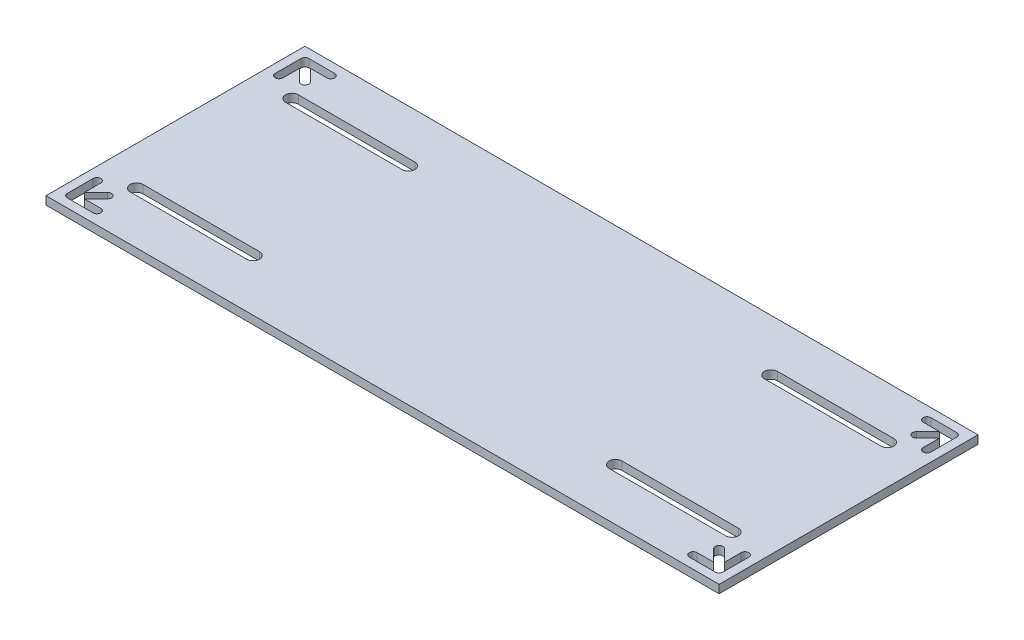
SolidWorks part; units mm, degrees
ref_plane "Front Plane" through (0, 0, 0) normal (0, 0, 1) x (1, 0, 0)
ref_plane "Top Plane" through (0, 0, 0) normal (0, 1, 0) x (1, 0, 0)
ref_plane "Right Plane" through (0, 0, 0) normal (1, 0, 0) x (0, 0, -1)
sketch "Sketch1" plane through (0, 0, 0) normal (0, 1, 0) x (1, 0, 0)
  line L0 (0, -50) -> (0, 50) construction
  line L1 (130, -50) -> (-130, -50)
  line L2 (130, -50) -> (130, 50)
  line L3 (130, 50) -> (-130, 50)
  line L4 (-130, -50) -> (-130, 50)
  line L5 (130, -50) -> (-130, 50) construction
  line L6 (130, 50) -> (-130, -50) construction
  line L7 (-130, 0) -> (130, 0) construction
  point P0 (0, 0)
  dimension "D1" = 260
  dimension "D2" = 100
extrude "Base" add sketch "Sketch1" along normal blind 3.175 contours L3 L4 L1 L2
sketch "Sketch2" plane through (0, 3.175, 0) normal (0, 1, 0) x (1, 0, 0)
  line L0 (0, -50) -> (0, 50) construction
  line L1 (130, -50) -> (-130, -50) construction
  line L2 (130, 50) -> (-130, 50) construction
  line L3 (-130, 0) -> (130, 0) construction
  line L4 (-130, -50) -> (-130, 50) construction
  line L5 (130, -50) -> (130, 50) construction
  line L6 (-115, 30) -> (-70, 30) construction
  line L7 (-115, 32.5) -> (-70, 32.5)
  line L8 (-115, 27.5) -> (-70, 27.5)
  line L9 (-115, -30) -> (-70, -30) construction
  line L12 (-115, -32.5) -> (-70, -32.5)
  line L13 (-115, -27.5) -> (-70, -27.5)
  line L14 (115, 30) -> (70, 30) construction
  line L15 (115, 32.5) -> (70, 32.5)
  line L16 (115, 27.5) -> (70, 27.5)
  line L17 (115, -30) -> (70, -30) construction
  line L18 (115, -32.5) -> (70, -32.5)
  line L19 (115, -27.5) -> (70, -27.5)
  arc A0 (-115, 32.5) -> (-115, 27.5) centre (-115, 30) ccw
  arc A1 (-70, 27.5) -> (-70, 32.5) centre (-70, 30) ccw
  arc A4 (-115, -32.5) -> (-115, -27.5) centre (-115, -30) cw
  arc A5 (-70, -27.5) -> (-70, -32.5) centre (-70, -30) cw
  arc A6 (115, 32.5) -> (115, 27.5) centre (115, 30) cw
  arc A7 (70, 27.5) -> (70, 32.5) centre (70, 30) cw
  arc A8 (115, -32.5) -> (115, -27.5) centre (115, -30) ccw
  arc A9 (70, -27.5) -> (70, -32.5) centre (70, -30) ccw
  point P14 (-92.5, 30)
  point P21 (-92.5, -30)
  point P28 (92.5, 30)
  point P35 (92.5, -30)
  dimension "D1" = 2.5
  dimension "D2" = 30
  dimension "D4" = 70
  dimension "D5" = 115
extrude "Slots" cut sketch "Sketch2" against normal through all
sketch "Sketch3" plane through (0, 3.175, 0) normal (0, 1, 0) x (1, 0, 0)
  line L0 (-130, 50) -> (-78.4181, -1.5819) construction
  line L1 (130, 50) -> (-130, 50) construction
  line L2 (-125.1502, 45.1502) -> (-115.1502, 45.1502) construction
  line L3 (-125.1502, 46.6502) -> (-115.1502, 46.6502)
  line L5 (-125.1502, 45.1502) -> (-125.1502, 35.1502) construction
  line L6 (-123.6502, 41.5289) -> (-123.6502, 35.1502)
  line L7 (-126.6502, 45.1502) -> (-126.6502, 35.1502)
  line L8 (-125.1502, 45.1502) -> (-118.0791, 38.0791) construction
  line L10 (-123.6502, 41.5289) -> (-119.1398, 37.0185)
  line L11 (-121.5289, 43.6502) -> (-117.0185, 39.1398)
  line L12 (-121.5289, 43.6502) -> (-115.1502, 43.6502)
  arc A0 (-125.1502, 46.6502) -> (-126.6502, 45.1502) centre (-125.1502, 45.1502) ccw
  arc A1 (-115.1502, 43.6502) -> (-115.1502, 46.6502) centre (-115.1502, 45.1502) ccw
  arc A3 (-126.6502, 35.1502) -> (-123.6502, 35.1502) centre (-125.1502, 35.1502) ccw
  arc A5 (-119.1398, 37.0185) -> (-117.0185, 39.1398) centre (-118.0791, 38.0791) ccw
  point P7 (-120.1502, 45.1502)
  point P12 (-125.1502, 40.1502)
  point P21 (-121.6147, 41.6147)
  dimension "D3" = 1.5
  dimension "D1" = 45
  dimension "D2" = 10
extrude "Mount Holes" cut sketch "Sketch3" against normal blind 3.175
mirror "Mirror1" about plane through (0, 0, 0) normal (1, 0, 0) of "Mount Holes"
mirror "Mirror2" about plane through (0, 0, 0) normal (0, 0, 1) of "Mirror1", "Mount Holes"
